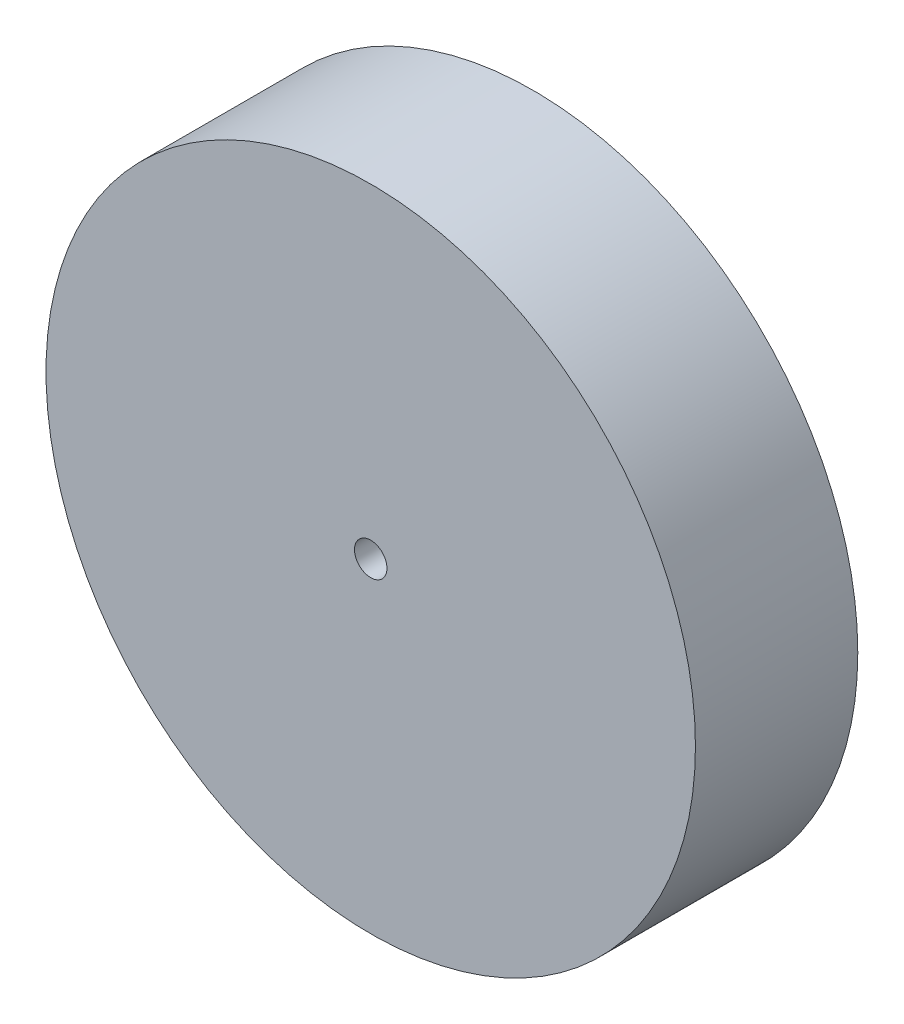
SolidWorks part; units mm, degrees
ref_plane "Front Plane" through (0, 0, 0) normal (0, 0, 1) x (1, 0, 0)
ref_plane "Top Plane" through (0, 0, 0) normal (0, 1, 0) x (1, 0, 0)
ref_plane "Right Plane" through (0, 0, 0) normal (1, 0, 0) x (0, 0, -1)
sketch "Sketch1" plane through (0, 0, 0) normal (0, 0, 1) x (1, 0, 0)
  circle A0 centre (0, 0) radius 10
  dimension "D1" = 20
extrude "Boss-Extrude1" add sketch "Sketch1" along normal blind 5
sketch "Sketch2" plane through (0, 0, 5) normal (0, 0, 1) x (1, 0, 0)
  circle A0 centre (0, 0) radius 0.5
  dimension "D1" = 1
extrude "Cut-Extrude1" cut sketch "Sketch2" against normal blind 5
sketch "Sketch3" plane through (0, 0, 0) normal (0, 0, -1) x (-1, 0, 0)
  circle A0 centre (0, 0) radius 1.7
  dimension "D1" = 3.4
extrude "Cut-Extrude2" cut sketch "Sketch3" against normal blind 0.2
